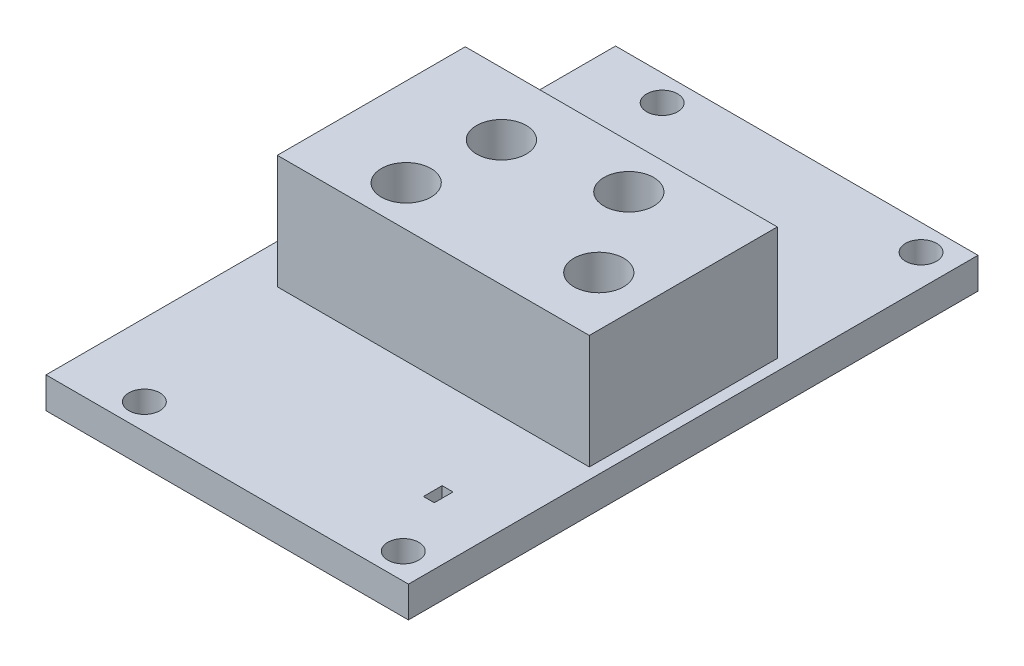
SolidWorks part; units mm, degrees
ref_plane "Front Plane" through (0, 0, 0) normal (0, 0, 1) x (1, 0, 0)
ref_plane "Top Plane" through (0, 0, 0) normal (0, 1, 0) x (1, 0, 0)
ref_plane "Right Plane" through (0, 0, 0) normal (1, 0, 0) x (0, 0, -1)
sketch "Sketch1" plane through (0, 0, 0) normal (0, 1, 0) x (1, 0, 0)
  line L0 (-10.5, 25) -> (14.5, -25) construction
  line L1 (-17.5, -27.5) -> (17.5, -27.5)
  line L2 (-17.5, -27.5) -> (-17.5, 27.5)
  line L3 (-17.5, 27.5) -> (17.5, 27.5)
  line L4 (17.5, -27.5) -> (17.5, 27.5)
  line L5 (17.5, 0) -> (-17.5, 0) construction
  line L6 (10.8934, -17.6387) -> (11.9467, -17.6387)
  line L7 (-10.5, -25) -> (14.5, -25) construction
  line L8 (-10.5, -25) -> (-10.5, 25) construction
  line L9 (-10.5, 25) -> (14.5, 25) construction
  line L10 (14.5, -25) -> (14.5, 25) construction
  line L11 (10.8934, -17.6387) -> (10.8934, -19.4488)
  line L12 (10.8934, -19.4488) -> (11.9467, -19.4488)
  line L13 (11.9467, -17.6387) -> (11.9467, -19.4488)
  line L14 (10.8934, -17.6387) -> (11.9467, -19.4488) construction
  line L15 (10.8934, -19.4488) -> (11.9467, -17.6387) construction
  circle A0 centre (14.5, 25) radius 1.5
  circle A1 centre (-10.5, 25) radius 1.5
  circle A2 centre (14.5, -25) radius 1.5
  circle A3 centre (-10.5, -25) radius 1.5
  point P0 (0, 0)
  point P6 (0, 0)
  point P15 (11.42, -18.5438)
  point P16 (0, 0)
  point P25 (0, 27.5)
  point P27 (14.5, 0)
  point P28 (-17.5, 0)
  point P29 (11.42, -18.5438)
  dimension "D3" = 3
  dimension "D1" = 25
  dimension "D2" = 50
  dimension "D4" = 7
  dimension "D13" = 35
  dimension "D14" = 55
extrude "Boss-Extrude1" add sketch "Sketch1" along normal blind 3
sketch "Sketch2" plane through (0, 3, 0) normal (0, 1, 0) x (1, 0, 0)
  line L1 (-13.6936, 9.1821) -> (16.4369, 9.1821)
  line L2 (-13.6936, 9.1821) -> (-13.6936, -8.9691)
  line L3 (-13.6936, -8.9691) -> (16.4369, -8.9691)
  line L4 (16.4369, 9.1821) -> (16.4369, -8.9691)
extrude "Boss-Extrude2" add sketch "Sketch2" along normal blind 11
sketch "Sketch4" plane through (0, 0, 0) normal (0, -1, 0) x (1, 0, 0)
  line L1 (14.2012, 8.8296) -> (-11.7715, 8.8296)
  line L2 (14.2012, 8.8296) -> (14.2012, -8.906)
  line L3 (14.2012, -8.906) -> (-11.7715, -8.906)
  line L4 (-11.7715, 8.8296) -> (-11.7715, -8.906)
extrude "Cut-Extrude2" cut sketch "Sketch4" against normal blind 4
sketch "Sketch6" plane through (0, 0, 0) normal (0, -1, 0) x (1, 0, 0)
  line L0 (-17.5, 0) -> (17.5, 0) construction
  line L5 (-17.5, -27.5) -> (-17.5, 27.5) construction
  line L14 (17.5, 27.5) -> (17.5, -27.5) construction
  line L15 (0, 27.7475) -> (0, -25.4862) construction
  line L16 (17.5, -27.5) -> (-17.5, -27.5) construction
  line L17 (-17.5, 27.5) -> (17.5, 27.5) construction
  line L18 (-17.5, -27.5) -> (-17.5, 27.5) construction
  circle A12 centre (11.63, 3.25) radius 2.4
  circle A13 centre (-5.17, 5.05) radius 2.4
  circle A14 centre (-4.17, -3.15) radius 2.4
  circle A15 centre (6.33, -4.95) radius 2.4
  point P0 (0, 0)
  dimension "D3" = 30.75
  dimension "D8" = 4.8
  dimension "D2" = 13.33
  dimension "D4" = 22.45
  dimension "D6" = 12.33
  dimension "D7" = 5.87
  dimension "D9" = 22.55
  dimension "D10" = 11.17
  dimension "D11" = 24.35
extrude "Cut-Extrude3" cut sketch "Sketch6" against normal through all both and the other way through all
sketch "Sketch7" plane through (0, 4, 0) normal (0, -1, 0) x (1, 0, 0)
  circle A0 centre (-5.17, 5.05) radius 3.75
  circle A1 centre (-4.17, -3.15) radius 3.75
  circle A2 centre (6.33, -4.95) radius 3.75
  circle A3 centre (11.63, 3.25) radius 3.75
  dimension "D1" = 7.5
extrude "Cut-Extrude4" cut sketch "Sketch7" against normal blind 2.5 and the other way through all
